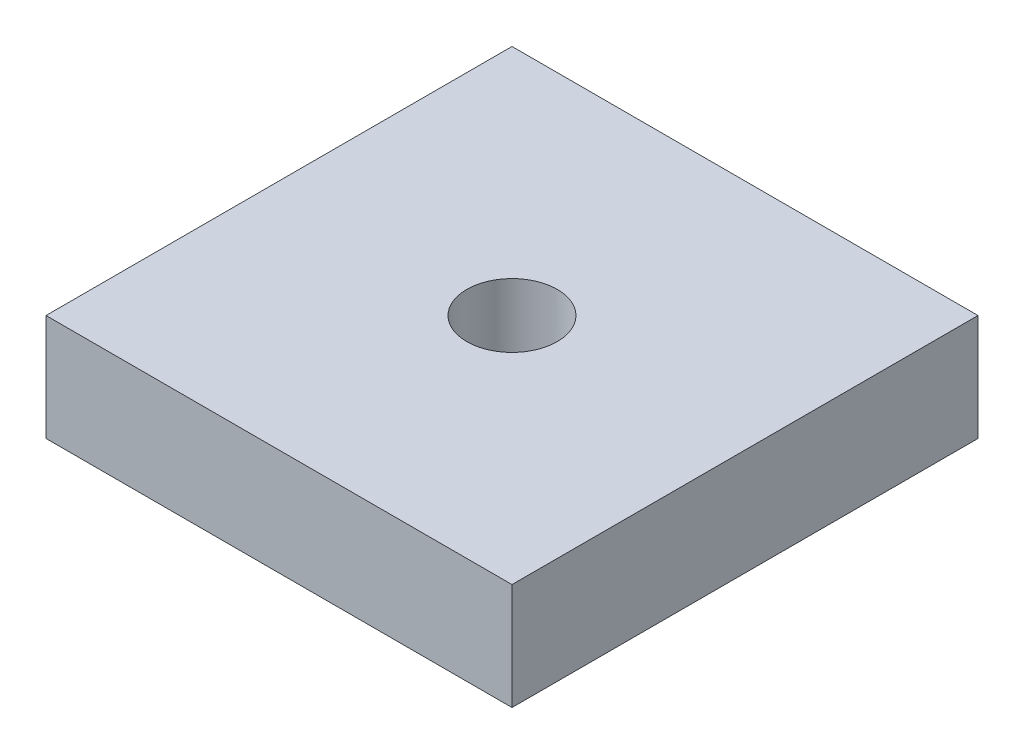
SolidWorks part; units mm, degrees
ref_plane "前视基准面" through (0, 0, 0) normal (0, 0, 1) x (1, 0, 0)
ref_plane "上视基准面" through (0, 0, 0) normal (0, 1, 0) x (1, 0, 0)
ref_plane "右视基准面" through (0, 0, 0) normal (1, 0, 0) x (0, 0, -1)
sketch "草图1" plane through (0, 0, 0) normal (0, 1, 0) x (1, 0, 0)
  line L1 (-17.5, -17.5) -> (17.5, -17.5)
  line L2 (-17.5, -17.5) -> (-17.5, 17.5)
  line L3 (-17.5, 17.5) -> (17.5, 17.5)
  line L4 (17.5, -17.5) -> (17.5, 17.5)
  line L5 (-17.5, -17.5) -> (17.5, 17.5) construction
  line L6 (-17.5, 17.5) -> (17.5, -17.5) construction
  point P0 (0, 0)
  dimension "D1" = 35
extrude "凸台-拉伸1" add sketch "草图1" along normal blind 8
hole_wizard "M8 螺纹孔1" positions "草图2" profile "草图3" tap size "M8" standard "GB" end condition up to next
sketch "草图2" plane through (0, 8, 0) normal (0, 1, 0) x (1, 0, 0)
  point P0 (0, 0)
sketch "草图3" plane through (0, 8, 0) normal (1, 0, 0) x (0, 0, 1)
  line L0 (0, 0) -> (0, 8)
  line L1 (0, 8) -> (3.4, 8)
  line L2 (3.4, 8) -> (3.4, 0)
  line L5 (3.4, 0) -> (0, 0)
  line L11 (0, -6.35) -> (0, 107.95) construction
  dimension "通孔螺纹孔钻头直径" = 6.8
  dimension "通孔螺纹孔钻头深度" = 8
cosmetic thread "孔螺纹线1" parameters "D2"=8
